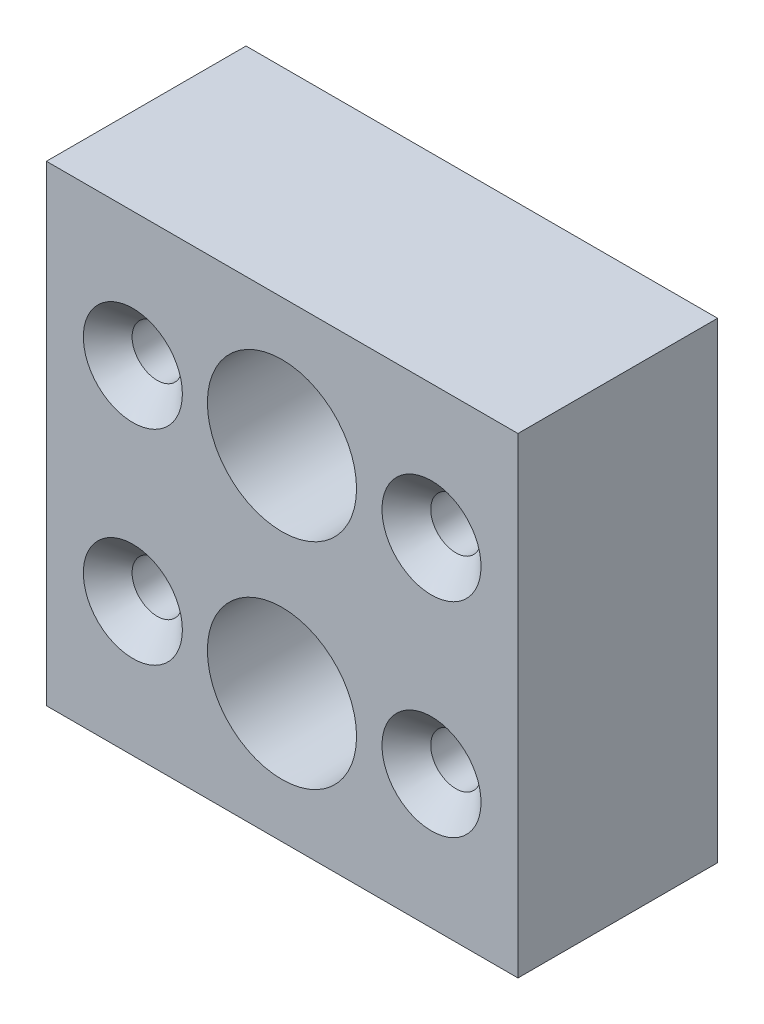
SolidWorks part; units mm, degrees
ref_plane "Front Plane" through (0, 0, 0) normal (0, 0, 1) x (1, 0, 0)
ref_plane "Top Plane" through (0, 0, 0) normal (0, 1, 0) x (1, 0, 0)
ref_plane "Right Plane" through (0, 0, 0) normal (1, 0, 0) x (0, 0, -1)
sketch "Sketch1" plane through (0, 0, 0) normal (0, 0, 1) x (1, 0, 0)
  line L1 (15, -15) -> (-15, -15)
  line L2 (15, -15) -> (15, 15)
  line L3 (15, 15) -> (-15, 15)
  line L4 (-15, -15) -> (-15, 15)
  line L6 (15, -8.75) -> (15, 8.75) construction
  line L7 (-8.75, -15) -> (8.75, -15) construction
  line L8 (-15, 8.75) -> (-15, -8.75) construction
  line L9 (8.75, 15) -> (-8.75, 15) construction
  arc A0 (-8.9105, -5.421) -> (-10.0895, -7.579) centre (-9.5, -6.5) ccw construction
  arc A1 (-10.0895, -7.579) -> (-8.9105, -5.421) centre (-9.5, -6.5) ccw construction
  arc A2 (-8.9105, 7.579) -> (-10.0895, 5.421) centre (-9.5, 6.5) ccw construction
  arc A3 (-10.0895, 5.421) -> (-8.9105, 7.579) centre (-9.5, 6.5) ccw construction
  arc A4 (10.0895, 7.579) -> (8.9105, 5.421) centre (9.5, 6.5) ccw construction
  arc A5 (8.9105, 5.421) -> (10.0895, 7.579) centre (9.5, 6.5) ccw construction
  arc A6 (10.0895, -5.421) -> (8.9105, -7.579) centre (9.5, -6.5) ccw construction
  arc A7 (8.9105, -7.579) -> (10.0895, -5.421) centre (9.5, -6.5) ccw construction
  arc A8 (-8.9105, -5.421) -> (-10.0895, -7.579) centre (-9.5, -6.5) ccw
  arc A9 (-10.0895, -7.579) -> (-8.9105, -5.421) centre (-9.5, -6.5) ccw
  arc A10 (-8.9105, 7.579) -> (-10.0895, 5.421) centre (-9.5, 6.5) ccw
  arc A11 (-10.0895, 5.421) -> (-8.9105, 7.579) centre (-9.5, 6.5) ccw
  arc A12 (10.0895, 7.579) -> (8.9105, 5.421) centre (9.5, 6.5) ccw
  arc A13 (8.9105, 5.421) -> (10.0895, 7.579) centre (9.5, 6.5) ccw
  arc A14 (10.0895, -5.421) -> (8.9105, -7.579) centre (9.5, -6.5) ccw
  arc A15 (8.9105, -7.579) -> (10.0895, -5.421) centre (9.5, -6.5) ccw
  spline S0 degree 2 poles (2024.3147, 2202.4489) (38.9785, -59.6733) (-2.1805, -8.5565) (-2.5302, -8.1222) (-2.6867, -7.5883) (-2.8436, -7.0533) (-2.7839, -6.5001) (-2.7241, -5.9458) (-2.4572, -5.4576) (-2.1899, -4.9684) (-1.7565, -4.6195) (-1.3222, -4.2698) (-0.7883, -4.1133) (-0.2533, -3.9564) (0.2999, -4.0161) (65.6517, -11.0684) (-780.1663, -2899.9323) knots -14.611133 -14.611133 -14.611133 0.125 0.125 0.25 0.25 0.375 0.375 0.5 0.5 0.625 0.625 0.75 0.75 0.875 0.875 15.620381 15.620381 15.620381 only from (-1.3424, -9.2572) to (1.3424, -4.3428) construction
  spline S1 degree 2 poles (-2024.3147, -2216.0489) (-38.9785, 46.0733) (2.1805, -5.0435) (2.5302, -5.4778) (2.6867, -6.0117) (2.8436, -6.5467) (2.7839, -7.0999) (2.7241, -7.6542) (2.4572, -8.1424) (2.1899, -8.6316) (1.7565, -8.9805) (1.3222, -9.3302) (0.7883, -9.4867) (0.2533, -9.6436) (-0.2999, -9.5839) (-65.6517, -2.5316) (780.1663, 2886.3323) knots -14.611133 -14.611133 -14.611133 0.125 0.125 0.25 0.25 0.375 0.375 0.5 0.5 0.625 0.625 0.75 0.75 0.875 0.875 15.620381 15.620381 15.620381 only from (1.3424, -4.3428) to (-1.3424, -9.2572) construction
  spline S2 degree 2 poles (-2024.3147, -2202.4489) (-38.9785, 59.6733) (2.1805, 8.5565) (2.5302, 8.1222) (2.6867, 7.5883) (2.8436, 7.0533) (2.7839, 6.5001) (2.7241, 5.9458) (2.4572, 5.4576) (2.1899, 4.9684) (1.7565, 4.6195) (1.3222, 4.2698) (0.7883, 4.1133) (0.2533, 3.9564) (-0.2999, 4.0161) (-65.6517, 11.0684) (780.1663, 2899.9323) knots -14.611133 -14.611133 -14.611133 0.125 0.125 0.25 0.25 0.375 0.375 0.5 0.5 0.625 0.625 0.75 0.75 0.875 0.875 15.620381 15.620381 15.620381 only from (1.3424, 9.2572) to (-1.3424, 4.3428) construction
  spline S3 degree 2 poles (2024.3147, 2216.0489) (38.9785, -46.0733) (-2.1805, 5.0435) (-2.5302, 5.4778) (-2.6867, 6.0117) (-2.8436, 6.5467) (-2.7839, 7.0999) (-2.7241, 7.6542) (-2.4572, 8.1424) (-2.1899, 8.6316) (-1.7565, 8.9805) (-1.3222, 9.3302) (-0.7883, 9.4867) (-0.2533, 9.6436) (0.2999, 9.5839) (65.6517, 2.5316) (-780.1663, -2886.3323) knots -14.611133 -14.611133 -14.611133 0.125 0.125 0.25 0.25 0.375 0.375 0.5 0.5 0.625 0.625 0.75 0.75 0.875 0.875 15.620381 15.620381 15.620381 only from (-1.3424, 4.3428) to (1.3424, 9.2572) construction
  spline S4 degree 2 poles (-1.3424, -9.2572) (-1.8314, -8.9901) (-2.1805, -8.5565) (-2.5302, -8.1222) (-2.6867, -7.5883) (-2.8436, -7.0533) (-2.7839, -6.5001) (-2.7241, -5.9458) (-2.4572, -5.4576) (-2.1899, -4.9684) (-1.7565, -4.6195) (-1.3222, -4.2698) (-0.7883, -4.1133) (-0.2533, -3.9564) (0.2999, -4.0161) (0.8539, -4.0759) (1.3424, -4.3428) knots 0 0 0 0.125 0.125 0.25 0.25 0.375 0.375 0.5 0.5 0.625 0.625 0.75 0.75 0.875 0.875 1 1 1
  spline S5 degree 2 poles (1.3424, -4.3428) (1.8314, -4.6099) (2.1805, -5.0435) (2.5302, -5.4778) (2.6867, -6.0117) (2.8436, -6.5467) (2.7839, -7.0999) (2.7241, -7.6542) (2.4572, -8.1424) (2.1899, -8.6316) (1.7565, -8.9805) (1.3222, -9.3302) (0.7883, -9.4867) (0.2533, -9.6436) (-0.2999, -9.5839) (-0.8539, -9.5241) (-1.3424, -9.2572) knots 0 0 0 0.125 0.125 0.25 0.25 0.375 0.375 0.5 0.5 0.625 0.625 0.75 0.75 0.875 0.875 1 1 1
  spline S6 degree 2 poles (1.3424, 9.2572) (1.8314, 8.9901) (2.1805, 8.5565) (2.5302, 8.1222) (2.6867, 7.5883) (2.8436, 7.0533) (2.7839, 6.5001) (2.7241, 5.9458) (2.4572, 5.4576) (2.1899, 4.9684) (1.7565, 4.6195) (1.3222, 4.2698) (0.7883, 4.1133) (0.2533, 3.9564) (-0.2999, 4.0161) (-0.8539, 4.0759) (-1.3424, 4.3428) knots 0 0 0 0.125 0.125 0.25 0.25 0.375 0.375 0.5 0.5 0.625 0.625 0.75 0.75 0.875 0.875 1 1 1
  spline S7 degree 2 poles (-1.3424, 4.3428) (-1.8314, 4.6099) (-2.1805, 5.0435) (-2.5302, 5.4778) (-2.6867, 6.0117) (-2.8436, 6.5467) (-2.7839, 7.0999) (-2.7241, 7.6542) (-2.4572, 8.1424) (-2.1899, 8.6316) (-1.7565, 8.9805) (-1.3222, 9.3302) (-0.7883, 9.4867) (-0.2533, 9.6436) (0.2999, 9.5839) (0.8539, 9.5241) (1.3424, 9.2572) knots 0 0 0 0.125 0.125 0.25 0.25 0.375 0.375 0.5 0.5 0.625 0.625 0.75 0.75 0.875 0.875 1 1 1
extrude "Boss-Extrude1" add sketch "Sketch1" along normal blind 12.7
sketch "Sketch4" plane through (0, 0, 12.7) normal (0, 0, 1) x (1, 0, 0)
  point P8 (-9.5, -6.5)
  point P11 (-9.5, 6.5)
  point P13 (9.5, 6.5)
  point P15 (9.5, -6.5)
hole_wizard "CSK for M3 Flat Head Machine Screw1" positions "Sketch5" profile "Sketch6" countersink size "M3" standard "ANSI Metric" end condition through all
sketch "Sketch5" plane through (0, 0, 12.7) normal (0, 0, 1) x (1, 0, 0)
  point P0 (-9.5, -6.5)
  point P3 (-9.5, 6.5)
  point P6 (9.5, 6.5)
  point P9 (9.5, -6.5)
sketch "Sketch6" plane through (-9.5, -6.5, 12.7) normal (1, 0, 0) x (0, -1, 0)
  line L0 (0, 0) -> (0, 12.705)
  line L1 (0, 12.705) -> (1.6, 12.705)
  line L2 (1.6, 12.705) -> (1.6, 1.55)
  line L3 (1.6, 1.55) -> (3.15, 0)
  line L5 (3.15, 0) -> (0, 0)
  line L6 (-1.6, 1.55) -> (-3.15, 0) construction
  line L11 (0, -6.35) -> (0, 107.95) construction
  dimension "Thru Hole Dia." = 3.2
  dimension "Thru Hole Depth" = 12.705
  dimension "Near C'Sink Dia." = 6.3
  dimension "Near C'Sink Angle" = 90
sketch "Sketch7" plane through (0, 0, 12.7) normal (0, 0, 1) x (1, 0, 0)
  circle A0 centre (-0.0143, -6.8261) radius 2.8298
  circle A1 centre (-0.0143, -6.8261) radius 5.1435
  spline S4 degree 2 poles (1.3424, -4.3428) (0.8539, -4.0759) (0.2999, -4.0161) (-0.2533, -3.9564) (-0.7883, -4.1133) (-1.3222, -4.2698) (-1.7565, -4.6195) (-2.1899, -4.9684) (-2.4572, -5.4576) (-2.7241, -5.9458) (-2.7839, -6.5001) (-2.8436, -7.0533) (-2.6867, -7.5883) (-2.5302, -8.1222) (-2.1805, -8.5565) (-1.8314, -8.9901) (-1.3424, -9.2572) knots 0 0 0 0.125 0.125 0.25 0.25 0.375 0.375 0.5 0.5 0.625 0.625 0.75 0.75 0.875 0.875 1 1 1 construction
  dimension "D1" = 5.6595
  dimension "D2" = 10.287
hole_wizard "1/8 NPT Tapped Hole1" positions "Sketch8" profile "Sketch10" size "1/8" standard "ANSI Inch"
sketch "Sketch8" plane through (0, 0, 12.7) normal (0, 0, 1) x (1, 0, 0)
  point P0 (-0.0143, -6.8261)
cosmetic thread "Hole Thread1" parameters "D1"=6.92, "D2"=10.2867
sketch "Sketch10" plane through (-0.0143, -6.8261, 12.7) normal (1, 0, 0) x (0, -1, 0)
  line L0 (0, 0) -> (0, 12.1347)
  line L1 (4.2164, 9.6012) -> (0, 12.1347)
  line L2 (-4.2164, 9.6012) -> (0, 12.1347) construction
  line L3 (4.2164, 9.6012) -> (4.2164, 6.92)
  line L4 (4.2164, 6.92) -> (4.5374, 6.92)
  line L5 (4.5374, 6.92) -> (4.7446, 0)
  line L6 (-4.5374, 6.92) -> (-4.7446, 0) construction
  line L7 (4.7446, 0) -> (0, 0)
  line L8 (0, -6.35) -> (0, 107.95) construction
  line L11 (-4.2164, 6.92) -> (-4.5374, 6.92) construction
  dimension "Tap Drill Dia." = 8.4328
  dimension "Tap Drill Depth" = 9.6012
  dimension "Thread Dia." = 9.4892
  dimension "Thread Angle" = 3.43
  dimension "Thread Depth" = 6.92
  dimension "Drill Angle" = 118
ref_plane "Plane4" through (0, 0, 0) normal (0, 1, 0) x (1, 0, 0)
mirror "Mirror1" about plane through (0, 0, 0) normal (0, 1, 0) of "1/8 NPT Tapped Hole1"
